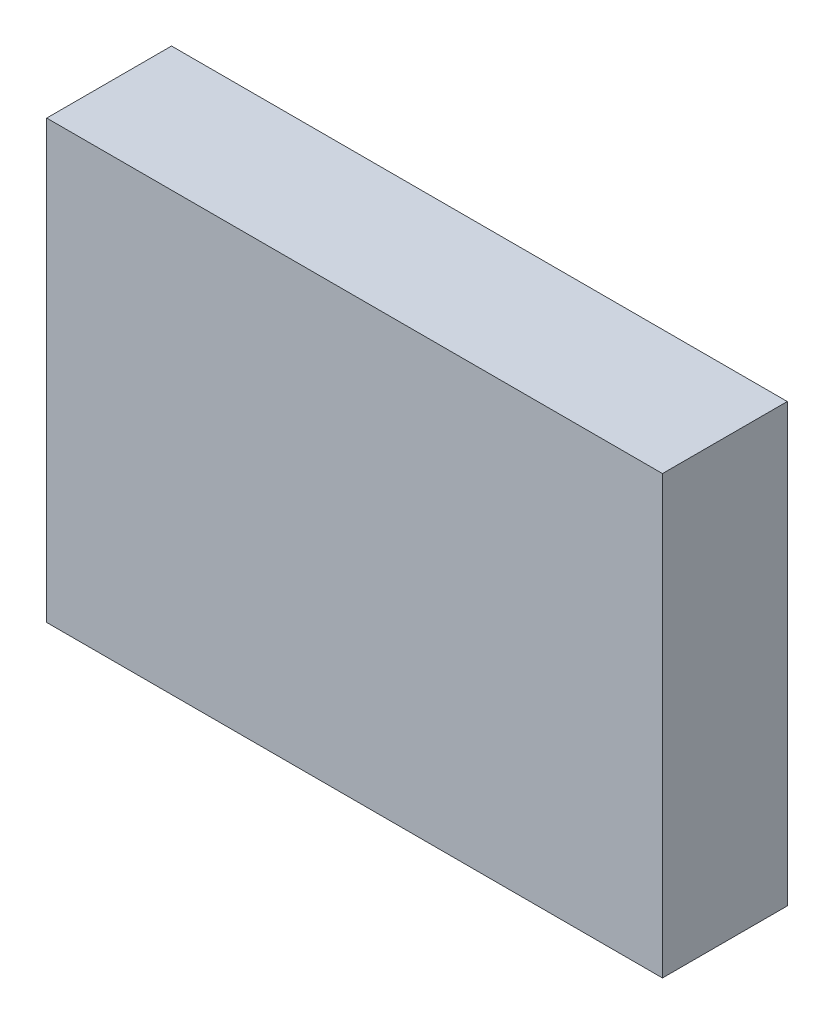
SolidWorks part; units mm, degrees
ref_plane "正面" through (0, 0, 0) normal (0, 0, 1) x (1, 0, 0)
ref_plane "平面" through (0, 0, 0) normal (0, 1, 0) x (1, 0, 0)
ref_plane "右側面" through (0, 0, 0) normal (1, 0, 0) x (0, 0, -1)
sketch "ｽｹｯﾁ1" plane through (0, 0, 0) normal (0, 0, 1) x (1, 0, 0)
  line L1 (-74, 52.5) -> (74, 52.5)
  line L2 (-74, 52.5) -> (-74, -52.5)
  line L3 (-74, -52.5) -> (74, -52.5)
  line L4 (74, 52.5) -> (74, -52.5)
  line L5 (-74, 52.5) -> (74, -52.5) construction
  line L6 (-74, -52.5) -> (74, 52.5) construction
  point P0 (0, 0)
  dimension "D1" = 105
  dimension "D2" = 148
extrude "ﾎﾞｽ - 押し出し1" add sketch "ｽｹｯﾁ1" along normal blind 30
